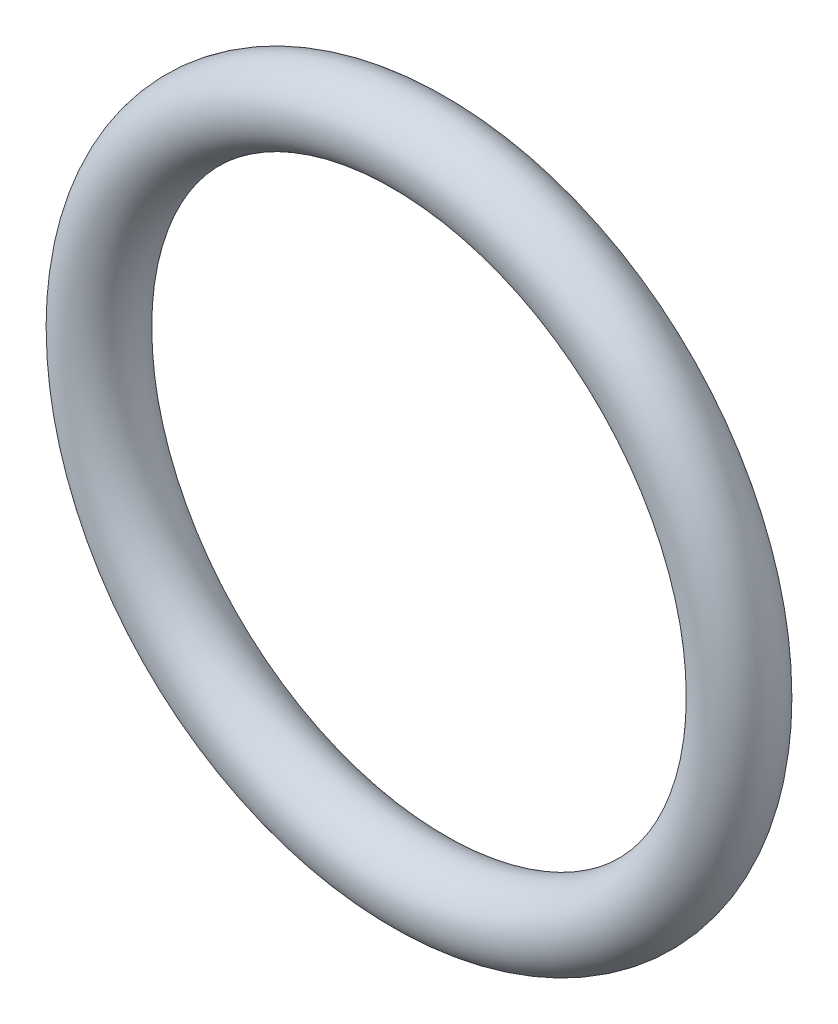
SolidWorks part; units mm, degrees
ref_plane "Front Plane" through (0, 0, 0) normal (0, 0, 1) x (1, 0, 0)
ref_plane "Top Plane" through (0, 0, 0) normal (0, 1, 0) x (1, 0, 0)
ref_plane "Right Plane" through (0, 0, 0) normal (1, 0, 0) x (0, 0, -1)
sketch "Sketch1" plane through (0, 0, 0) normal (0, 0, 1) x (1, 0, 0)
  circle A0 centre (0, 0) radius 16.5
  circle A1 centre (0, 0) radius 13.0468
  dimension "D1" = 33
  dimension "D2" = 3.4532
sketch "Sketch3" plane through (0, 0, 0) normal (1, 0, 0) x (0, 0, -1)
  line L0 (0, 16.5) -> (0, 13.05) construction
  line L1 (0, 16.5) -> (0, -16.5) construction
  circle A0 centre (0, 14.775) radius 1.725
  dimension "D1" = 3.45
ref_axis "Axis1" through (0, 0, 1.0652) along (0, 0, -1)
revolve "Revolve1" add sketch "Sketch3" angle 360 about axis through (0, 0, 1.0652) along (0, 0, -1)
